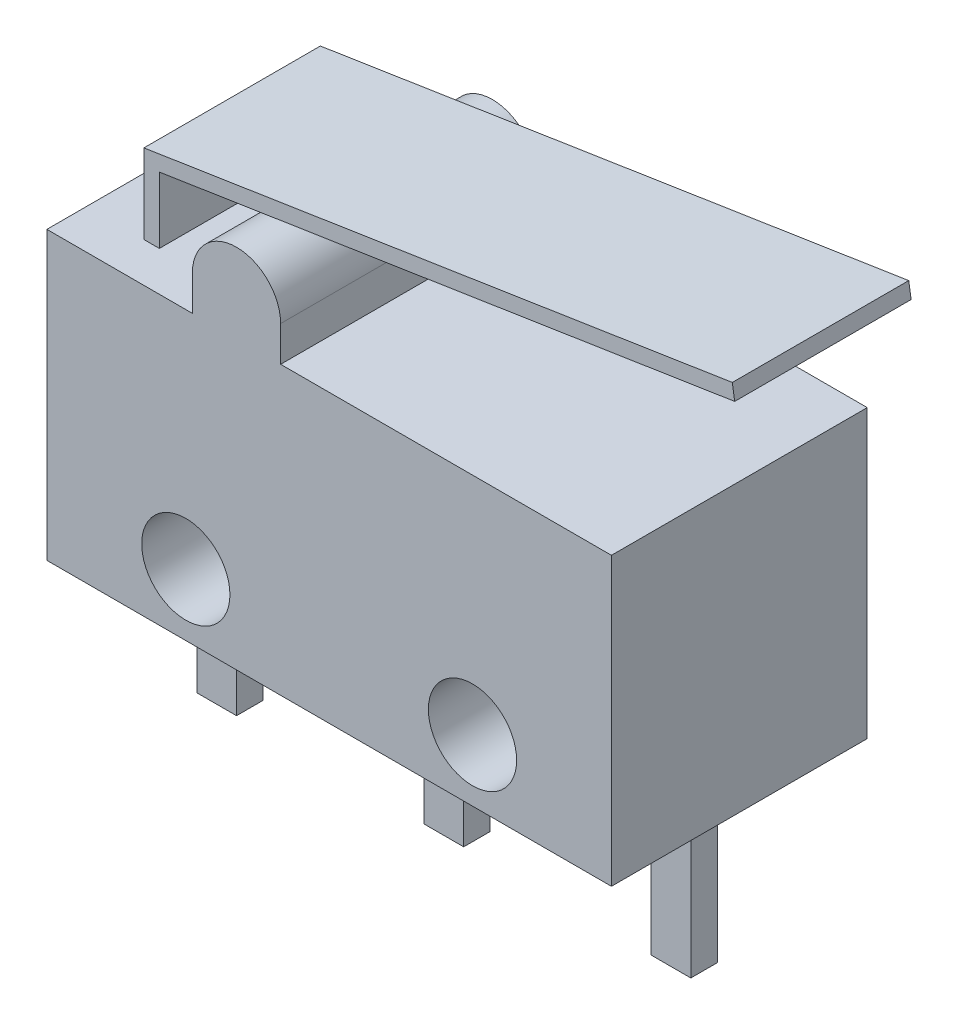
SolidWorks part; units mm, degrees
ref_plane "Front Plane" through (0, 0, 0) normal (0, 0, 1) x (1, 0, 0)
ref_plane "Top Plane" through (0, 0, 0) normal (0, 1, 0) x (1, 0, 0)
ref_plane "Right Plane" through (0, 0, 0) normal (1, 0, 0) x (0, 0, -1)
sketch "Sketch1" plane through (0, 0, 0) normal (0, 1, 0) x (1, 0, 0)
  line L1 (-6.4, -2.9) -> (6.4, -2.9)
  line L2 (-6.4, -2.9) -> (-6.4, 2.9)
  line L3 (-6.4, 2.9) -> (6.4, 2.9)
  line L4 (6.4, -2.9) -> (6.4, 2.9)
  line L5 (-6.4, -2.9) -> (6.4, 2.9) construction
  line L6 (-6.4, 2.9) -> (6.4, -2.9) construction
  point P0 (0, 0)
  dimension "D1" = 5.8
  dimension "D2" = 12.8
extrude "Boss-Extrude1" add sketch "Sketch1" along normal blind 6.5
sketch "Sketch2" plane through (0, 0, 2.9) normal (0, 0, 1) x (1, 0, 0)
  line L0 (0, 6.5) -> (0, 0) construction
  line L1 (-6.4, 6.5) -> (6.4, 6.5) construction
  line L2 (-6.4, 0) -> (6.4, 0) construction
  circle A0 centre (-3.25, 1.4) radius 1
  circle A1 centre (3.25, 1.4) radius 1
  point P8 (0, 0)
  dimension "D1" = 2
  dimension "D2" = 1.4
  dimension "D3" = 6.5
extrude "Cut-Extrude1" cut sketch "Sketch2" against normal blind 16.5
sketch "Sketch3" plane through (0, 0, 0) normal (0, -1, 0) x (1, 0, 0)
  line L0 (0, 2.9) -> (0, -2.9) construction
  line L1 (-4.7, 0.3) -> (-5.6, 0.3)
  line L2 (-4.7, 0.3) -> (-4.7, -0.3)
  line L3 (-4.7, -0.3) -> (-5.6, -0.3)
  line L4 (-5.6, 0.3) -> (-5.6, -0.3)
  line L5 (-6.4, 0) -> (6.4, 0) construction
  line L6 (6.4, 2.9) -> (6.4, -2.9) construction
  line L8 (0.45, 0.3) -> (-0.45, 0.3)
  line L9 (0.45, 0.3) -> (0.45, -0.3)
  line L10 (0.45, -0.3) -> (-0.45, -0.3)
  line L11 (-0.45, 0.3) -> (-0.45, -0.3)
  line L12 (-6.4, 2.9) -> (6.4, 2.9) construction
  line L13 (6.4, -2.9) -> (-6.4, -2.9) construction
  line L14 (4.7, -0.3) -> (5.6, -0.3)
  line L15 (5.6, 0.3) -> (5.6, -0.3)
  line L16 (4.7, 0.3) -> (5.6, 0.3)
  line L17 (4.7, 0.3) -> (4.7, -0.3)
  point P10 (0, 0.3)
  point P11 (-5.6, 0)
  point P23 (-0.45, 0)
  point P24 (-5.15, 0.3)
  dimension "D1" = 0.6
  dimension "D2" = 0.9
  dimension "D3" = 5.15
extrude "Boss-Extrude2" add sketch "Sketch3" along normal blind 3.5
sketch "Sketch4" plane through (0, 0, 2.9) normal (0, 0, 1) x (1, 0, 0)
  line L0 (-3.1, 6.5) -> (-3.1, 7.3)
  line L1 (-6.4, 6.5) -> (6.4, 6.5) construction
  line L2 (-3.1, 6.5) -> (-1.1, 6.5)
  line L3 (-1.1, 7.3) -> (-1.1, 6.5)
  line L4 (-6.4, 6.5) -> (-6.4, 0) construction
  arc A0 (-1.1, 7.3) -> (-3.1, 7.3) centre (-2.1, 7.3) ccw
  dimension "D2" = 1
  dimension "D1" = 0.8
  dimension "D3" = 4.3
extrude "Boss-Extrude3" add sketch "Sketch4" against normal up to vertex (5.8 mm away)
sketch "Sketch5" plane through (0, 0, 0) normal (0, 0, 1) x (1, 0, 0)
  line L0 (-5.1, 6.5) -> (-5.1, 8.3)
  line L1 (-6.4, 6.5) -> (-3.1, 6.5) construction
  line L2 (-5.1, 8.3) -> (8.2412, 10.3647)
  line L3 (8.2412, 10.3647) -> (8.2947, 10.0188)
  line L4 (8.2947, 10.0188) -> (-4.75, 8)
  line L5 (-4.75, 8) -> (-4.75, 6.5)
  line L6 (-4.75, 6.5) -> (-5.1, 6.5)
  line L7 (-6.4, 6.5) -> (-6.4, 0) construction
  dimension "D1" = 1.3
  dimension "D2" = 13.5
  dimension "D3" = 1.8
  dimension "D4" = 1.5
extrude "Boss-Extrude4" add sketch "Sketch5" along normal mid plane 4
